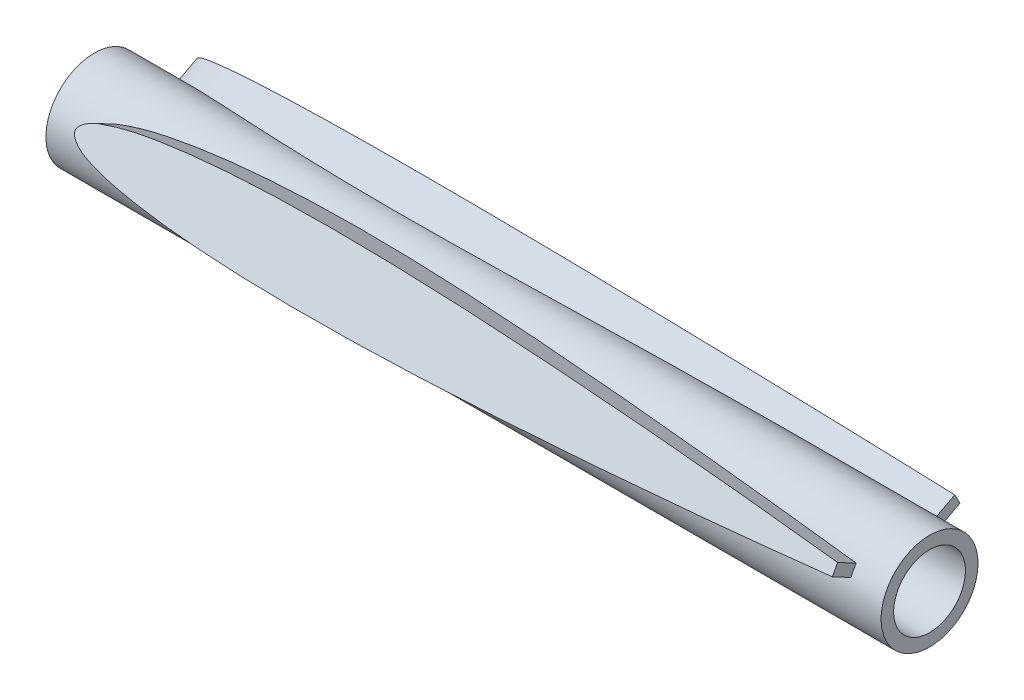
SolidWorks part; units mm, degrees
ref_plane "Front Plane" through (0, 0, 0) normal (0, 0, 1) x (1, 0, 0)
ref_plane "Top Plane" through (0, 0, 0) normal (0, 1, 0) x (1, 0, 0)
ref_plane "Right Plane" through (0, 0, 0) normal (1, 0, 0) x (0, 0, -1)
sketch "Эскиз4" plane through (0, 0, 0) normal (0, 0, 1) x (1, 0, 0)
  line L0 (0, 0) -> (-190.9268, 0) construction
ref_plane "Плоскость2" through (0, 0, 0) normal (0, -0.4695, 0.8829) x (-1, 0, 0)
curve "Кривая2"
  spline degree 3 poles (195, 0.1446, 0.0769) (191.7503, 0.4076, 0.2167) (185.2523, 0.9335, 0.4963) (172.2543, 1.9127, 1.0169) (156.0064, 3.0366, 1.6144) (136.5058, 4.2319, 2.2499) (117.0061, 5.2717, 2.8027) (97.5059, 6.116, 3.2517) (78.0051, 6.72, 3.5728) (61.7506, 6.9306, 3.6848) (48.7484, 6.8474, 3.6405) (38.9957, 6.6202, 3.5197) (29.2371, 6.1855, 3.2886) (21.113, 5.5745, 2.9638) (14.6037, 4.8451, 2.576) (9.7375, 4.1386, 2.2003) (5.5568, 3.2162, 1.7099) (2.2726, 2.2745, 1.2092) (-1.296, 0, 0) (2.2726, -2.2745, -1.2092) (5.5568, -3.2162, -1.7099) (9.7375, -4.1386, -2.2003) (14.6037, -4.8451, -2.576) (21.113, -5.5745, -2.9638) (29.2371, -6.1855, -3.2886) (38.9957, -6.6202, -3.5197) (48.7484, -6.8474, -3.6405) (61.7506, -6.9306, -3.6848) (78.0051, -6.72, -3.5728) (97.5059, -6.116, -3.2517) (117.0061, -5.2717, -2.8027) (136.5058, -4.2319, -2.2499) (156.0064, -3.0366, -1.6144) (172.2543, -1.9127, -1.0169) (185.2523, -0.9335, -0.4963) (191.7503, -0.4076, -0.2167) (195, -0.1446, -0.0769) knots 0 0 0 0 0.024876 0.049742 0.099443 0.149112 0.198751 0.248359 0.297937 0.347491 0.372267 0.397051 0.421859 0.446731 0.45922 0.471791 0.48456 0.491195 0.5 0.508805 0.51544 0.528209 0.54078 0.553269 0.578141 0.602949 0.627733 0.652509 0.702063 0.751641 0.801249 0.850888 0.900557 0.950258 0.975124 1 1 1 1
sketch "Эскиз5" plane through (0, 0, 0) normal (0, -0.4695, 0.8829) x (-1, 0, 0)
  line L0 (-182, -1.3314) -> (-182, 1.3314)
  line L1 (0, 0) -> (0, -20.2138) construction
  spline S0 degree 3 poles (-1090.5141, -2820.9233) (-613.9595, 82.5122) (-398.4311, 17.1316) (-172.2543, -2.1663) (-156.0064, -3.439) (-136.5058, -4.7928) (-117.0061, -5.9704) (-97.5059, -6.9267) (-78.0051, -7.6107) (-61.7506, -7.8493) (-48.7484, -7.755) (-38.9957, -7.4977) (-29.2371, -7.0053) (-21.113, -6.3134) (-14.6037, -5.4873) (-9.7375, -4.6872) (-5.5568, -3.6425) (-2.2726, -2.5759) (1.296, 0) (-2.2726, 2.5759) (-5.5568, 3.6425) (-9.7375, 4.6872) (-14.6037, 5.4873) (-21.113, 6.3134) (-29.2371, 7.0053) (-38.9957, 7.4977) (-48.7484, 7.755) (-61.7506, 7.8493) (-78.0051, 7.6107) (-97.5059, 6.9267) (-117.0061, 5.9704) (-136.5058, 4.7928) (-156.0064, 3.439) (-172.2543, 2.1663) (-398.4306, -17.1316) (-613.9586, -82.5119) (-1090.511, 2820.9046) knots -1.630961 -1.630961 -1.630961 -1.630961 0.024876 0.049742 0.099443 0.149112 0.198751 0.248359 0.297937 0.347491 0.372267 0.397051 0.421859 0.446731 0.45922 0.471791 0.48456 0.491195 0.5 0.508805 0.51544 0.528209 0.54078 0.553269 0.578141 0.602949 0.627733 0.652509 0.702063 0.751641 0.801249 0.850888 0.900557 0.950258 0.975124 2.630958 2.630958 2.630958 2.630958 only from (-195, -0.1638) to (-195, 0.1638) construction
  spline S1 degree 3 poles (-182, -1.3314) (-179.8337, -1.5187) (-171.1702, -2.2512) (-156.0064, -3.439) (-136.5058, -4.7928) (-117.0061, -5.9704) (-97.5059, -6.9267) (-78.0051, -7.6107) (-61.7506, -7.8493) (-48.7484, -7.755) (-38.9957, -7.4977) (-29.2371, -7.0053) (-21.113, -6.3134) (-14.6037, -5.4873) (-9.7375, -4.6872) (-5.5568, -3.6425) (-2.2726, -2.5759) (0, -0.9355) (0, 0) knots 0.033166 0.033166 0.033166 0.033166 0.049742 0.099443 0.149112 0.198751 0.248359 0.297937 0.347491 0.372267 0.397051 0.421859 0.446731 0.45922 0.471791 0.48456 0.491195 0.5 0.5 0.5 0.5
  spline S2 degree 3 poles (0, 0) (0, 0.9355) (-2.2726, 2.5759) (-5.5568, 3.6425) (-9.7375, 4.6872) (-14.6037, 5.4873) (-21.113, 6.3134) (-29.2371, 7.0053) (-38.9957, 7.4977) (-48.7484, 7.755) (-61.7506, 7.8493) (-78.0051, 7.6107) (-97.5059, 6.9267) (-117.0061, 5.9704) (-136.5058, 4.7928) (-156.0064, 3.439) (-171.1702, 2.2512) (-179.8337, 1.5187) (-182, 1.3314) knots 0.5 0.5 0.5 0.5 0.508805 0.51544 0.528209 0.54078 0.553269 0.578141 0.602949 0.627733 0.652509 0.702063 0.751641 0.801249 0.850888 0.900557 0.950258 0.966834 0.966834 0.966834 0.966834
  dimension "D1" = 182
sketch "Эскиз6" plane through (0, 0, 0) normal (1, 0, 0) x (0, 0, -1)
  line L0 (0, 0) -> (17.6146, 0) construction
  line L1 (0, 0) -> (-14.6569, -7.7932) construction
  line L2 (-14.6569, 0.8068) -> (-14.6569, -16.3932) construction
  circle A0 centre (-14.6569, -7.7932) radius 8.6
  circle A1 centre (-14.6569, -7.7932) radius 11.6
  point P3 (-11.6812, -11.7945)
  dimension "D2" = 17.2
  dimension "D3" = 8
  dimension "D1" = 28
  dimension "D4" = 3
extrude "Бобышка-Вытянуть1" add sketch "Эскиз6" along normal blind 190 and the other way blind 10
extrude "Бобышка-Вытянуть2" add sketch "Эскиз5" along normal up to body separate body
ref_plane "Плоскость3" through (0, 0, 14.6569) normal (0, 0, 1) x (1, 0, 0)
mirror "Зеркальное отражение1" about plane through (0, 0, 14.6569) normal (0, 0, 1) of "Бобышка-Вытянуть2"
equation "\"D6@Fus\"=\"DMotor\"+1.2"
equation "\"D1@Fus\"=\"FusLenght\""
equation "\"D2@Fus\"=\"MotorArm\""
equation "\"D4@Fus\"=\"DFus\""
equation "\"D5@Fus\" = \"FusCentralPartLenght\""
equation "\"D8@Fus\"=\"FusTubeHeight\""
equation "\"D9@Fus\"=\"DFusTube\"+1.2"
equation "\"D11@Fus\"=\"FusNoseLenght\""
equation "\"D3@Fus\"=\"WingOffset\""
equation "\"D19@Бобышка-Вытянуть1\" = \"CenterSectionLenght\" / 2"
equation "\"D4@FusCopy\" = \"FusTubeHeight\""
equation "\"D1@CentralPartCrossSection1\"=\"DFus\"*\"EllipseRatio\""
equation "\"D1@CentralPartCrossSection2\"=\"DFus\"*\"EllipseRatio\""
equation "\"D2@Frame\" = \"DFusTube\" + 1.2"
equation "\"DTailTube\"= 16мм'Диаметр трубки хвостового оперения"
equation "\"FusLenght\"= 700мм"
equation "\"DMotor\"= 35.2мм"
equation "\"MotorArm\"= 225мм"
equation "\"DFus\"= 130мм"
equation "\"DFusTube\"= 16мм'Диаметр трубки внутри фюзеляжа"
equation "\"FusTubeHeight\"= 30мм"
equation "\"FusCentralPartLenght\"= 350мм"
equation "\"FusNoseLenght\"= 170мм"
equation "\"WingOffset\"= 1мм'Расстояние от внутренней поверхности фюзеляжа до профиля крыла по вертикали"
equation "\"EllipseRatio\"= 1.1'Центральная часть фюзеляжа - эллипс. Этот параметр - отношение длин осей эллипса"
equation "\"FrameOffset\"= 0.6мм"
equation "\"DThreadedInsert\"= 3.6мм'Внешний диамер резьбовых втулок"
equation "\"CenterSectionLenght\"= 140мм'Длина центроплана"
equation "\"b\"= 1680мм'Размах"
equation "\"cwr\"= 236мм'Корневая хорда крыла"
equation "\"TR\"= 0.75'Сужение крыла"
equation "\"cwt\"= \"TR\" * \"cwr\"'Концевая хорда крыла"
equation "\"D3@Airfoil\"=\"cwr\""
equation "\"DWingMainSpar\"= 16мм'Диаметр главного лонжерона крыла"
equation "\"DWingSecondSpar\"= 8мм'Диаметр второго лонжерона крыла"
equation "\"WingSparsDistance\"= 80мм'Расстояния между отверстиями по лонжерон крыла"
equation "\"D7@Airfoil\"=\"DWingMainSpar\""
equation "\"D9@Airfoil\"=\"DWingSecondSpar\""
equation "\"D8@Airfoil\"=\"WingSparsDistance\"*2"
equation "\"c\"= 210мм'САХ крыла"
equation "\"D2@Эскиз6\"=\"DTailTube\"+1.2"
